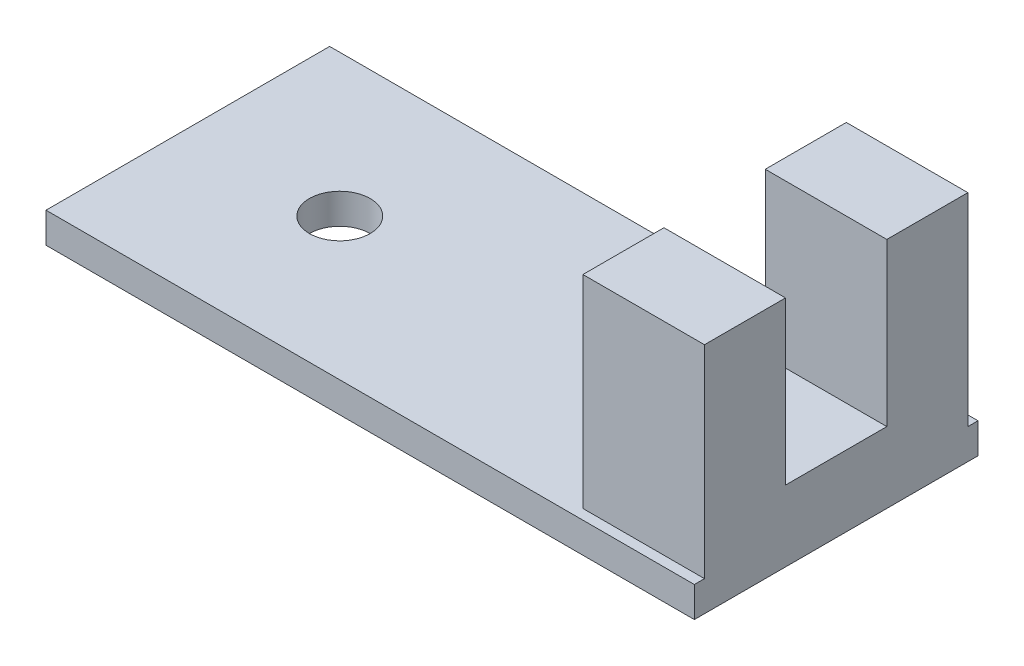
SolidWorks part; units mm, degrees
ref_plane "前视基准面" through (0, 0, 0) normal (0, 0, 1) x (1, 0, 0)
ref_plane "上视基准面" through (0, 0, 0) normal (0, 1, 0) x (1, 0, 0)
ref_plane "右视基准面" through (0, 0, 0) normal (1, 0, 0) x (0, 0, -1)
sketch "Sketch1" plane through (0, 0, 0) normal (0, 1, 0) x (1, 0, 0)
  line L0 (-8.5, 0) -> (0, 0) construction
  line L1 (-16, -7) -> (16, -7)
  line L2 (-16, -7) -> (-16, 7)
  line L3 (-16, 7) -> (16, 7)
  line L4 (16, -7) -> (16, 7)
  line L5 (-16, -7) -> (16, 7) construction
  line L6 (-16, 7) -> (16, -7) construction
  circle A0 centre (-8.5, 0) radius 1.5
  point P0 (0, 0)
  dimension "D3" = 3
  dimension "D1" = 32
  dimension "D2" = 14
  dimension "D4" = 7.5
extrude "Boss-Extrude1" add sketch "Sketch1" along normal blind 1.5
sketch "Sketch2" plane through (0, 1.5, 0) normal (0, 1, 0) x (1, 0, 0)
  line L0 (10, 6.5) -> (16, 6.5)
  line L1 (16, 6.5) -> (16, -6.5)
  line L2 (16, -6.5) -> (10, -6.5)
  line L3 (10, -6.5) -> (10, 6.5)
  line L4 (16, -7) -> (16, 7) construction
  point P3 (16, 0)
  dimension "D1" = 13
  dimension "D2" = 6
extrude "Boss-Extrude2" add sketch "Sketch2" along normal blind 2
sketch "Sketch3" plane through (0, 3.5, 0) normal (0, 1, 0) x (1, 0, 0)
  line L0 (16, -6.5) -> (16, 6.5) construction
  line L1 (10, 6.5) -> (16, 6.5)
  line L2 (10, 6.5) -> (10, 2.5)
  line L3 (10, 2.5) -> (16, 2.5)
  line L4 (16, 6.5) -> (16, 2.5)
  line L6 (10, -6.5) -> (16, -6.5)
  line L7 (10, -6.5) -> (10, -2.5)
  line L8 (10, -2.5) -> (16, -2.5)
  line L9 (16, -6.5) -> (16, -2.5)
  dimension "D1" = 4
extrude "Boss-Extrude3" add sketch "Sketch3" along normal blind 8
